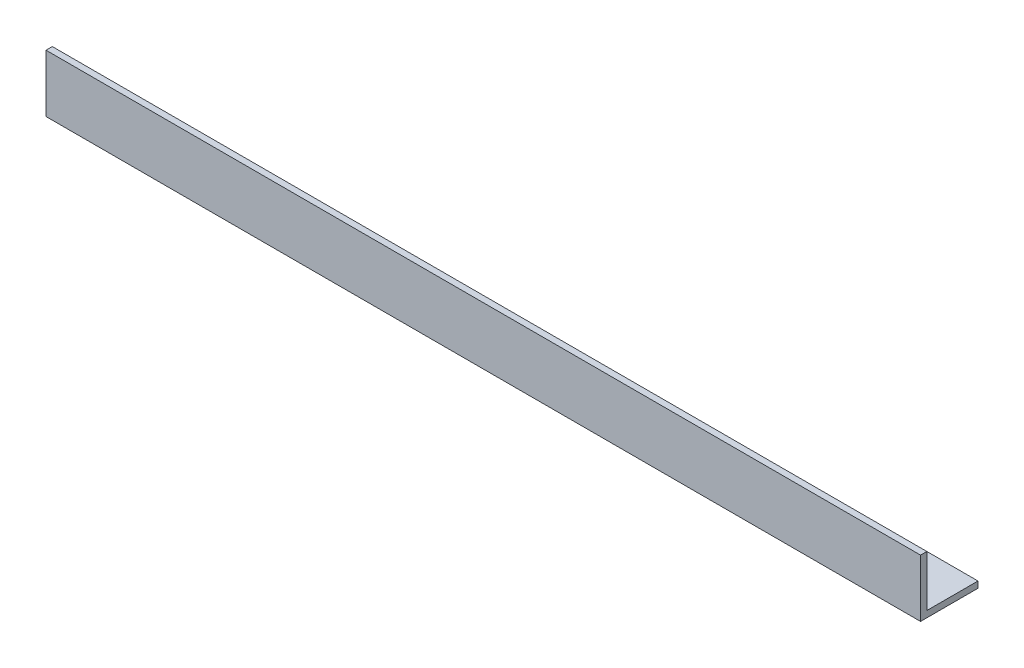
SolidWorks part; units mm, degrees
ref_plane "Front Plane" through (0, 0, 0) normal (0, 0, 1) x (1, 0, 0)
ref_plane "Top Plane" through (0, 0, 0) normal (0, 1, 0) x (1, 0, 0)
ref_plane "Right Plane" through (0, 0, 0) normal (1, 0, 0) x (0, 0, -1)
sketch "Sketch1" plane through (0, 0, 0) normal (0, 1, 0) x (1, 0, 0)
  line L1 (-193.294, 12.7) -> (193.294, 12.7)
  line L2 (-193.294, 12.7) -> (-193.294, -12.7)
  line L3 (-193.294, -12.7) -> (193.294, -12.7)
  line L4 (193.294, 12.7) -> (193.294, -12.7)
  line L5 (-193.294, 12.7) -> (193.294, -12.7) construction
  line L6 (-193.294, -12.7) -> (193.294, 12.7) construction
  line L7 (-193.294, -12.7) -> (193.294, -12.7)
  line L8 (-193.294, -12.7) -> (-193.294, -9.906)
  line L9 (-193.294, -9.906) -> (193.294, -9.906)
  line L10 (193.294, -12.7) -> (193.294, -9.906)
  point P0 (0, 0)
  dimension "D1" = 25.4
  dimension "D2" = 386.588
  dimension "D3" = 2.794
extrude "Boss-Extrude1" add sketch "Sketch1" along normal blind 2.794 contours L9 L2 L3 L4 | L2 L9 L4 L1
sketch "Sketch2" plane through (0, 2.794, 0) normal (0, 1, 0) x (1, 0, 0)
  line L0 (193.294, 12.7) -> (193.294, -12.7) construction
  line L1 (-193.294, -12.7) -> (193.294, -12.7)
  line L2 (-193.294, -12.7) -> (-193.294, -9.906)
  line L3 (-193.294, -9.906) -> (193.294, -9.906)
  line L4 (193.294, -12.7) -> (193.294, -9.906)
  dimension "D1" = 2.794
extrude "Boss-Extrude3" add sketch "Sketch2" along normal blind 22.606
sketch "Sketch3" plane through (0, 0, 0) normal (0, -1, 0) x (-1, 0, 0)
  line L0 (0, 12.7) -> (0, -12.7) construction
  line L1 (193.294, 12.7) -> (-193.294, 12.7) construction
  line L2 (193.294, -12.7) -> (-193.294, -12.7) construction
